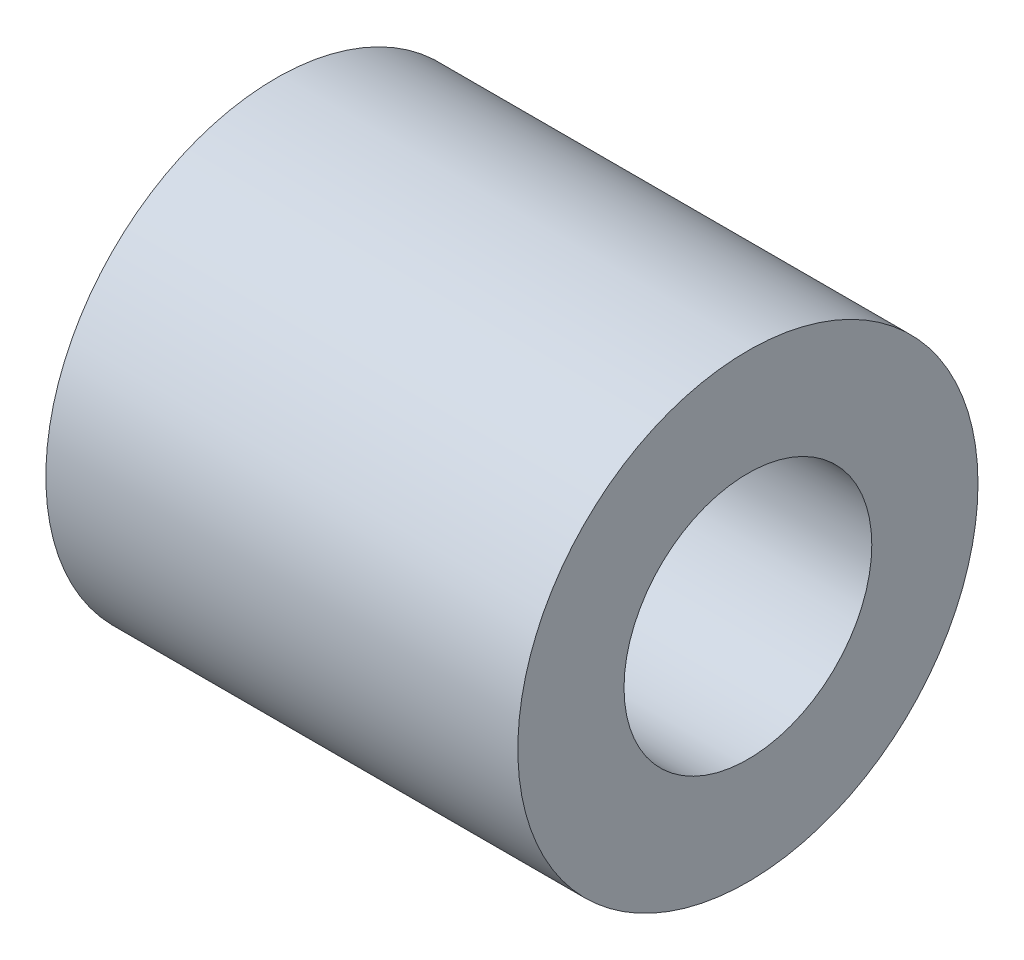
SolidWorks part; units mm, degrees
ref_plane "Front Plane" through (0, 0, 0) normal (0, 0, 1) x (1, 0, 0)
ref_plane "Top Plane" through (0, 0, 0) normal (0, 1, 0) x (1, 0, 0)
ref_plane "Right Plane" through (0, 0, 0) normal (1, 0, 0) x (0, 0, -1)
sketch "Sketch1" plane through (0, 0, 0) normal (1, 0, 0) x (0, 0, -1)
  circle A0 centre (0, 0) radius 3.15
  circle A1 centre (0, 0) radius 5.85
  dimension "D1" = 6.3
  dimension "D2" = 11.7
extrude "Boss-Extrude1" add sketch "Sketch1" along normal blind 12
